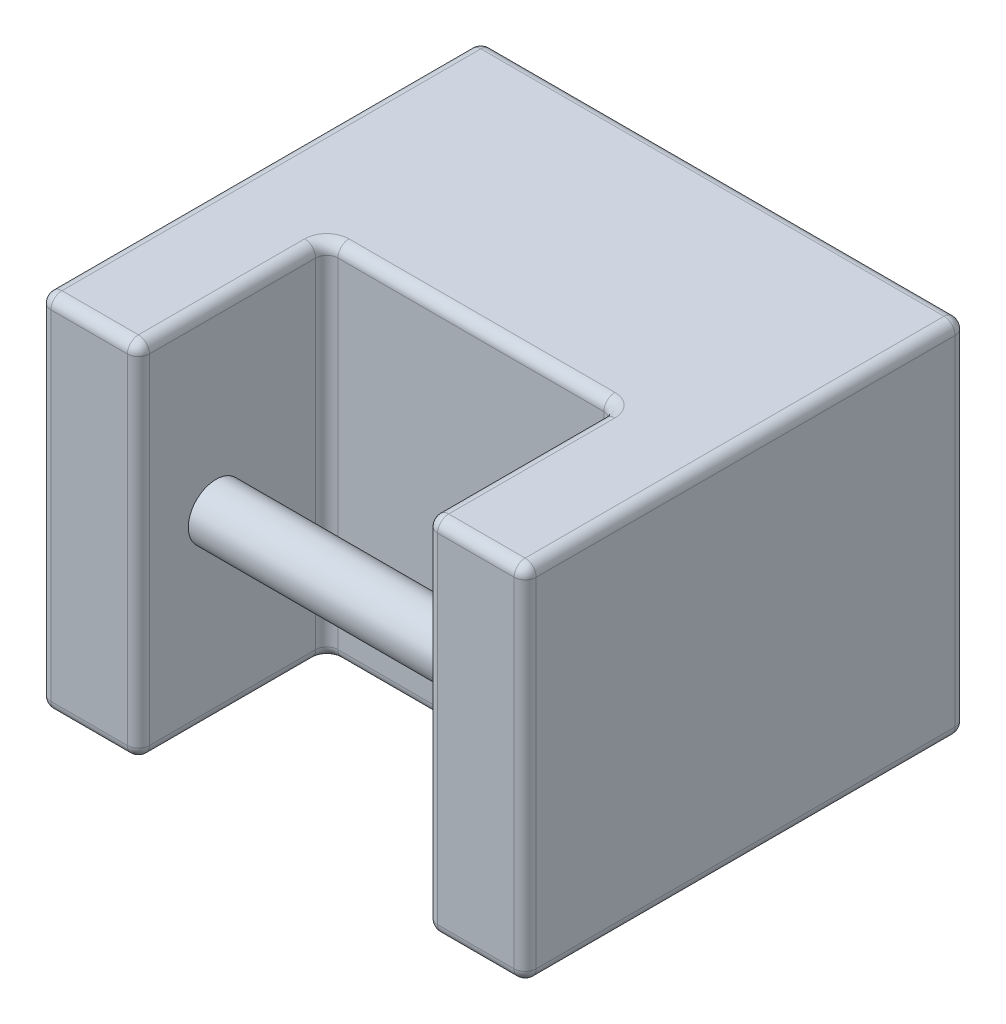
SolidWorks part; units mm, degrees
material "Q235-A"
ref_plane "前视基准面" through (0, 0, 0) normal (0, 0, 1) x (1, 0, 0)
ref_plane "上视基准面" through (0, 0, 0) normal (0, 1, 0) x (1, 0, 0)
ref_plane "右视基准面" through (0, 0, 0) normal (1, 0, 0) x (0, 0, -1)
sketch "草图1" plane through (0, 0, 0) normal (0, 0, 1) x (1, 0, 0)
  line L1 (-109.5, 81.5) -> (109.5, 81.5)
  line L2 (-109.5, 81.5) -> (-109.5, -81.5)
  line L3 (-109.5, -81.5) -> (109.5, -81.5)
  line L4 (109.5, 81.5) -> (109.5, -81.5)
  line L5 (-109.5, 81.5) -> (109.5, -81.5) construction
  line L6 (-109.5, -81.5) -> (109.5, 81.5) construction
  point P0 (0, 0)
  dimension "D1" = 219
  dimension "D2" = 163
extrude "凸台-拉伸1" add sketch "草图1" along normal blind 199
sketch "草图2" plane through (0, -81.5, 0) normal (0, -1, 0) x (1, 0, 0)
  line L0 (-109.5, 199) -> (109.5, 199) construction
  line L1 (-65, 284) -> (65, 284)
  line L2 (-65, 284) -> (-65, 114)
  line L3 (-65, 114) -> (65, 114)
  line L4 (65, 284) -> (65, 114)
  line L5 (-65, 284) -> (65, 114) construction
  line L6 (-65, 114) -> (65, 284) construction
  point P0 (0, 199)
  dimension "D1" = 85
  dimension "D2" = 130
extrude "切除-拉伸1" cut sketch "草图2" against normal through all
sketch "草图3" plane through (109.5, 0, 0) normal (1, 0, 0) x (0, 0, -1)
  line L0 (-199, 0) -> (-164, 0) construction
  line L1 (-199, -81.5) -> (-199, 81.5) construction
  circle A0 centre (-164, 0) radius 12.5
  dimension "D2" = 25
  dimension "D1" = 35
extrude "凸台-拉伸2" add sketch "草图3" against normal up to surface (219 mm away) up to face at (-109.5, 0, 99.5)
sketch "草图4" plane through (0, -81.5, 0) normal (0, -1, 0) x (1, 0, 0)
  line L0 (-51.215, 32.1803) -> (51.6869, 32.1803) construction
  text T0 "25Kg" font "汉仪长仿宋体" height 50
extrude "切除-拉伸2" cut sketch "草图4" against normal blind 0.1
fillet "圆角1" radius 5 24 edges at (65, -81.5, 156.5) (-87.25, -81.5, 199) (-65, 0, 199) (87.25, -81.5, 199) (65, 0, 199) (-65, 0, 114) (65, 0, 114) (0, -81.5, 114) (0, -81.5, 0) (-65, 81.5, 156.5) (-87.25, 81.5, 199) (0, 81.5, 0) (87.25, 81.5, 199) (65, 81.5, 156.5) (0, 81.5, 114) (-109.5, 81.5, 99.5) (-109.5, 0, 199) (-109.5, -81.5, 99.5) (-109.5, 0, 0) (109.5, -81.5, 99.5) (109.5, 0, 199) (109.5, 81.5, 99.5) (109.5, 0, 0) (-65, -81.5, 156.5)
